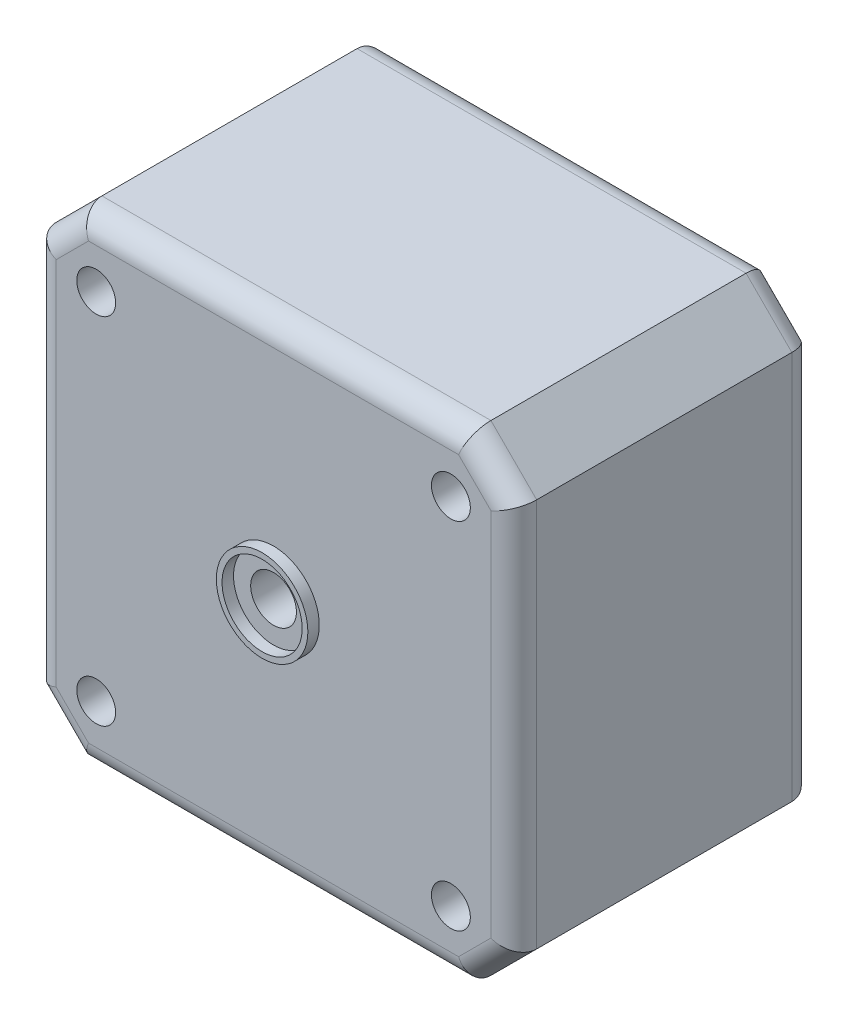
SolidWorks part; units mm, degrees
ref_plane "Спереди" through (0, 0, 0) normal (0, 0, 1) x (1, 0, 0)
ref_plane "Сверху" through (0, 0, 0) normal (0, 1, 0) x (1, 0, 0)
ref_plane "Справа" through (0, 0, 0) normal (1, 0, 0) x (0, 0, -1)
sketch "Эскиз4" plane through (0, 0, 0) normal (0, 0, 1) x (1, 0, 0)
  line L1 (-21, -21) -> (21, -21)
  line L2 (-21, -21) -> (-21, 21)
  line L3 (-21, 21) -> (21, 21)
  line L4 (21, -21) -> (21, 21)
  line L5 (-21, -21) -> (21, 21) construction
  line L6 (-21, 21) -> (21, -21) construction
  point P0 (0, 0)
extrude "Бобышка-Вытянуть2" add sketch "Эскиз4" along normal blind 26.3
chamfer "Фаска1" distance 4 angle 45 4 edges at (-21, -21, 13.15) (21, -21, 13.15) (21, 21, 13.15) (-21, 21, 13.15)
fillet "Скругление1" radius 2 16 edges at (-19, 19, 26.3) (0, 21, 26.3) (19, 19, 26.3) (21, 0, 26.3) (19, -19, 26.3) (0, -21, 26.3) (-19, -19, 26.3) (-21, 0, 26.3) (19, -19, 0) (21, 0, 0) (19, 19, 0) (0, 21, 0) (-19, 19, 0) (-21, 0, 0) (-19, -19, 0) (0, -21, 0)
sketch "Эскиз5" plane through (0, 0, 0) normal (0, 0, -1) x (-1, 0, 0)
  circle A0 centre (0, 0) radius 2
extrude "Вырез-Вытянуть1" cut sketch "Эскиз5" against normal through all
sketch "Эскиз6" plane through (0, 0, 0) normal (0, 0, -1) x (-1, 0, 0)
  circle A0 centre (0, 0) radius 4
  circle A1 centre (0, 0) radius 3.5
extrude "Бобышка-Вытянуть3" add sketch "Эскиз6" along normal blind 1
sketch "Эскиз7" plane through (0, 0, 26.3) normal (0, 0, 1) x (1, 0, 0)
  circle A0 centre (0, 0) radius 3.5
  circle A1 centre (0, 0) radius 4
extrude "Бобышка-Вытянуть4" add sketch "Эскиз7" along normal blind 1
sketch "Эскиз8" plane through (0, 0, 26.3) normal (0, 0, 1) x (1, 0, 0)
  line L1 (-15.5, -15.5) -> (15.5, -15.5)
  line L2 (-15.5, -15.5) -> (-15.5, 15.5)
  line L3 (-15.5, 15.5) -> (15.5, 15.5)
  line L4 (15.5, -15.5) -> (15.5, 15.5)
  line L5 (-15.5, -15.5) -> (15.5, 15.5) construction
  line L6 (-15.5, 15.5) -> (15.5, -15.5) construction
  point P0 (0, 0)
hole_wizard "Отверстие с зазором M31" positions "Эскиз10" profile "Эскиз11" hole size "M3" standard "Ansi Metric" end condition through all
sketch "Эскиз10" plane through (0, 0, 26.3) normal (0, 0, 1) x (1, 0, 0)
  point P0 (-15.5, 15.5)
sketch "Эскиз11" plane through (-15.5, 15.5, 26.3) normal (1, 0, 0) x (0, -1, 0)
  line L0 (0, 0) -> (0, 27.3)
  line L1 (0, 27.3) -> (1.7, 27.3)
  line L2 (1.7, 27.3) -> (1.7, 0)
  line L5 (1.7, 0) -> (0, 0)
  line L11 (0, -6.35) -> (0, 107.95) construction
  dimension "Диаметр сквозного отверстия" = 3.4
  dimension "Глубина сквозного отверстия" = 27.3
pattern_linear "Линейный массив1" count 2 spacing 31 along (1, 0, 0) count 2 spacing 31 along (0, -1, 0) of "Отверстие с зазором M31"
